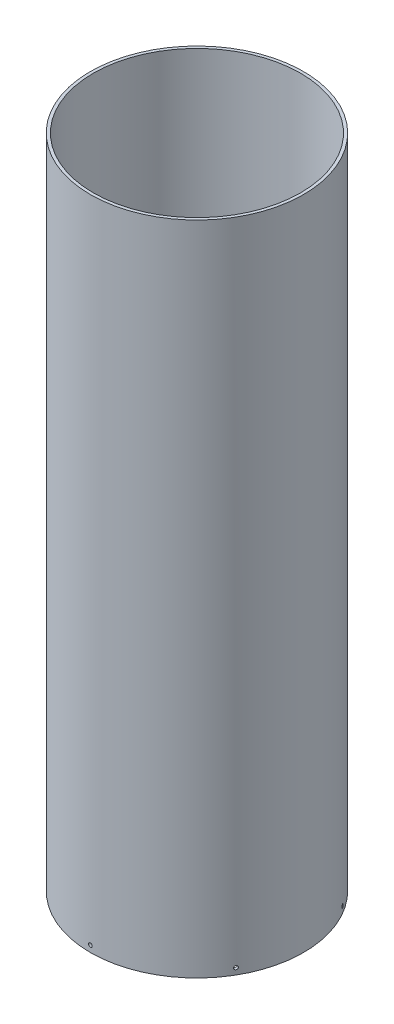
SolidWorks part; units mm, degrees
ref_plane "Front Plane" through (0, 0, 0) normal (0, 0, 1) x (1, 0, 0)
ref_plane "Top Plane" through (0, 0, 0) normal (0, 1, 0) x (1, 0, 0)
ref_plane "Right Plane" through (0, 0, 0) normal (1, 0, 0) x (0, 0, -1)
sketch "Sketch1" plane through (0, 0, 0) normal (0, 1, 0) x (1, 0, 0)
  circle A0 centre (0, 0) radius 76.2
  circle A1 centre (0, 0) radius 78.359
  dimension "D1" = 152.4
  dimension "D2" = 156.718
extrude "Boss-Extrude1" add sketch "Sketch1" along normal blind 482.6
ref_axis "Axis1" through (0, 482.6, 0) along (0, -1, 0)
sketch "Sketch2" plane through (0, 0, 0) normal (0, 0, 1) x (1, 0, 0)
  line L0 (0, 0) -> (0, 4.7625) construction
  circle A0 centre (0, 4.7625) radius 1.3526
  dimension "D1" = 2.7051
  dimension "D2" = 4.7625
extrude "Cut-Extrude1" cut sketch "Sketch2" against normal through all
pattern_circular "CirPattern1" count 6 over 360 about axis through (0, 482.6, 0) along (0, -1, 0) of "Cut-Extrude1"
equation "\"D1@Boss-Extrude1\"=\"Aft_Upper_Length\""
equation "\"AB_Coupling_Section_Length\"= 0.375in"
equation "\"AB_Coupler_Num_Screws\"= 6"
equation "\"AB_Coupling_Screw_Diameter\"= 0.1065in"
equation "\"AB_Coupler_OD_Length\"= 1in"
equation "\"AB_Coupler_Length\"= \"AB_Coupler_OD_Length\" + \"AB_Coupling_Section_Length\" * 2"
equation "\"D1@Sketch2\"=\"AB_Coupling_Screw_Diameter\""
equation "\"D2@Sketch2\"=\"AB_Coupling_Section_Length\"/2"
equation "\"D1@CirPattern1\"=\"AB_Coupler_Num_Screws\""
equation "\"Aft_Section_Length\"= 40in"
equation "\"Aft_Upper_Length\"= \"Aft_Section_Length\" - \"Aft_Lower_Length\" - \"AB_Coupler_OD_Length\""
equation "\"Aft_Lower_Length\"= 20in"
